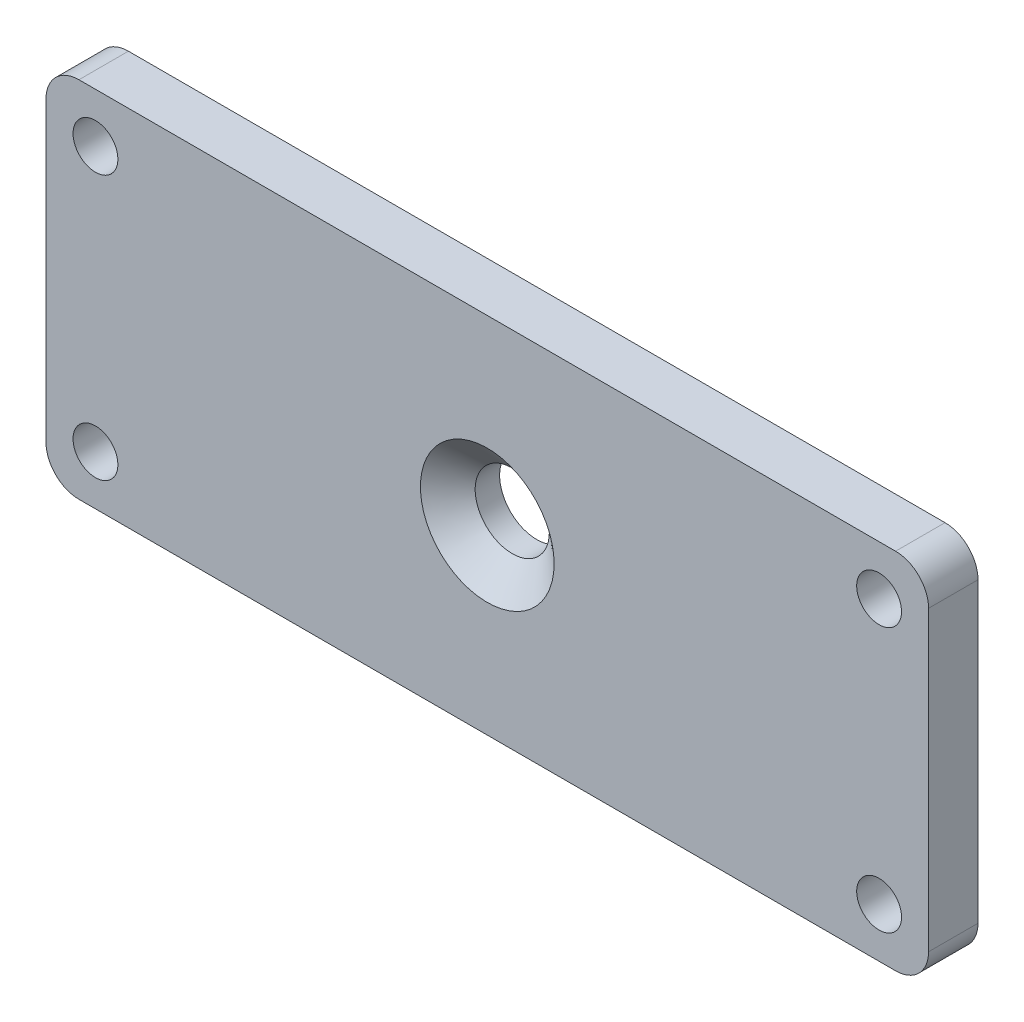
SolidWorks part; units mm, degrees
material "6061 Alloy"
ref_plane "Front Plane" through (0, 0, 0) normal (0, 0, 1) x (1, 0, 0)
ref_plane "Top Plane" through (0, 0, 0) normal (0, 1, 0) x (1, 0, 0)
ref_plane "Right Plane" through (0, 0, 0) normal (1, 0, 0) x (0, 0, -1)
sketch "Sketch1" plane through (0, 0, 0) normal (0, 1, 0) x (1, 0, 0)
  line L0 (0, 0) -> (50000, 0) construction
  line L1 (0, 0) -> (0, -50000) construction
  line L2 (-42.5, 0) -> (42.5, 0)
  line L5 (42.5, 0) -> (42.5, 4.7625)
  line L8 (42.5, 4.7625) -> (-42.5, 4.7625)
  line L11 (-42.5, 4.7625) -> (-42.5, 0)
  point P5 (-41.6551, 4.7625)
  point P6 (-41.6551, 0)
  point P8 (41.5196, 0)
  point P10 (0, 0)
  point P12 (13.5, 4.7625)
  point P13 (13.5, 4.7625)
  point P14 (-31.1267, 9.6209)
  point P17 (13.5, 4.7625)
  point P18 (41.6512, 4.7625)
  dimension "D5" = 4.7625
  dimension "D8" = 85
  dimension "D9" = 42.5
extrude "Boss-Extrude1" add sketch "Sketch1" along normal mid plane 35
sketch "Sketch2" plane through (0, 0, 0) normal (0, 0, 1) x (1, 0, 0)
  line L0 (0, 0) -> (35355.3391, -35355.3391) construction
  line L1 (0, 0) -> (35355.3391, 35355.3391) construction
  circle A0 centre (0, 0) radius 4
  circle A1 centre (0, 0) radius 11 construction
  circle A2 centre (-7.7782, 7.7782) radius 1.375
  circle A3 centre (7.7782, 7.7782) radius 1.375
  circle A4 centre (7.7782, -7.7782) radius 1.375
  circle A5 centre (-7.7782, -7.7782) radius 1.375
  dimension "D1" = 8
  dimension "D2" = 22
  dimension "D3" = 2.75
fillet "Fillet1" radius 3.175 4 edges at (42.5, -17.5, -2.3813) (-42.5, -17.5, -2.3813) (42.5, 17.5, -2.3813) (-42.5, 17.5, -2.3813)
sketch "Sketch3" plane through (0, 0, 0) normal (0, 0, 1) x (1, 0, 0)
  line L6 (-42.5, 14.325) -> (-42.5, -14.325) construction
  line L7 (-39.325, 17.5) -> (39.325, 17.5) construction
  line L8 (42.5, 14.325) -> (42.5, -14.325) construction
  line L9 (-39.325, -17.5) -> (39.325, -17.5) construction
  circle A0 centre (-37.7375, 12.7375) radius 2.159
  circle A1 centre (-37.7375, -12.7375) radius 2.159
  circle A2 centre (37.7375, 12.7375) radius 2.159
  circle A3 centre (37.7375, -12.7375) radius 2.159
  point P12 (-35.901, -17.5)
  point P13 (-42.5, -12.2107)
  point P16 (42.5, -10.5089)
  point P18 (42.5, 8.5683)
  point P20 (32.0617, 17.5)
  point P22 (-42.5, 4.041)
  point P25 (-32.3733, 17.5)
  point P28 (42.5, -10.5111)
  point P29 (34.6906, -17.5)
  dimension "D2" = 4.318
  dimension "D1" = 4.7625
  dimension "D6" = 4.7625
  dimension "D9" = 4.7625
  dimension "D5" = 4.7625
  dimension "D8" = 4.7625
  dimension "D4" = 4.7625
  dimension "D7" = 4.7625
  dimension "D3" = 4.7625
extrude "Cut-Extrude3" cut sketch "Sketch3" against normal blind 10
hole_wizard "CSK for 1/4 Flat Head Machine Screw (100)1" positions "Sketch8" profile "Sketch9" countersink size "1/4" standard "ANSI Inch" end condition through all
sketch "Sketch8" plane through (0, 0, 0) normal (0, 0, 1) x (1, 0, 0)
  point P0 (0, 0)
sketch "Sketch9" plane through (0, 0, 0) normal (1, 0, 0) x (0, -1, 0)
  line L0 (0, 0) -> (0, 4.7625)
  line L1 (0, 4.7625) -> (3.5712, 4.7625)
  line L2 (3.5712, 4.7625) -> (3.5712, 2.4063)
  line L3 (3.5712, 2.4063) -> (6.4389, 0)
  line L5 (6.4389, 0) -> (0, 0)
  line L6 (-3.5712, 2.4063) -> (-6.4389, 0) construction
  line L11 (0, -6.35) -> (0, 107.95) construction
  dimension "Thru Hole Dia." = 7.1425
  dimension "Thru Hole Depth" = 4.7625
  dimension "Near C'Sink Dia." = 12.8778
  dimension "Near C'Sink Angle" = 100
equation "\"D9@Sketch1\"=\"D8@Sketch1\"/2"
equation "\"D3@Sketch3\"=\"D1@Sketch3\""
equation "\"D4@Sketch3\"=\"D1@Sketch3\""
equation "\"D5@Sketch3\"=\"D1@Sketch3\""
equation "\"D6@Sketch3\"=\"D1@Sketch3\""
equation "\"D7@Sketch3\"=\"D1@Sketch3\""
equation "\"D8@Sketch3\"=\"D1@Sketch3\""
equation "\"D9@Sketch3\"=\"D1@Sketch3\""
